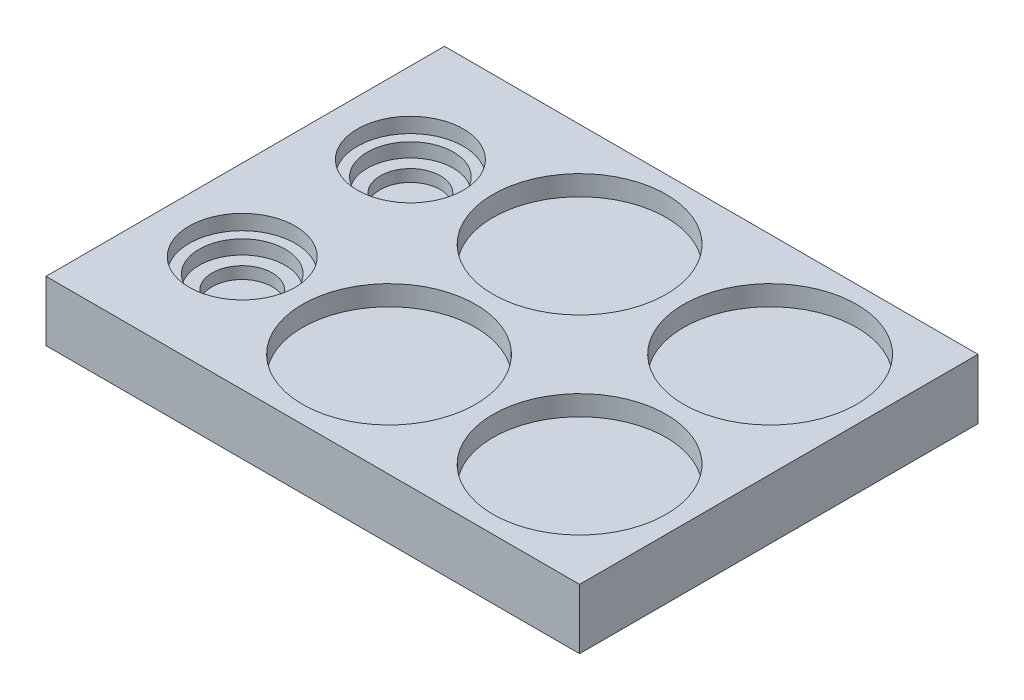
SolidWorks part; units mm, degrees
ref_plane "Спереди" through (0, 0, 0) normal (0, 0, 1) x (1, 0, 0)
ref_plane "Сверху" through (0, 0, 0) normal (0, 1, 0) x (1, 0, 0)
ref_plane "Справа" through (0, 0, 0) normal (1, 0, 0) x (0, 0, -1)
sketch "Эскиз1" plane through (0, 0, 0) normal (0, 1, 0) x (1, 0, 0)
  line L1 (0, 398) -> (533, 398)
  line L2 (0, 398) -> (0, 0)
  line L3 (0, 0) -> (533, 0)
  line L4 (533, 398) -> (533, 0)
  point P4 (0, 0)
  point P6 (0, 0)
  dimension "D1" = 533
  dimension "D2" = 398
extrude "Наполнитель" add sketch "Эскиз1" against normal blind 60
sketch "Эскиз2" plane through (0, 0, 0) normal (0, 1, 0) x (1, 0, 0)
  line L0 (429.1667, 380.6667) -> (429.1667, 398) construction
  line L1 (533, 398) -> (0, 398) construction
  line L2 (429.1667, 17.3333) -> (429.1667, 0) construction
  line L3 (0, 0) -> (533, 0) construction
  line L4 (515.6667, 294.1667) -> (533, 294.1667) construction
  line L5 (533, 0) -> (533, 398) construction
  line L6 (515.6667, 103.8333) -> (533, 103.8333) construction
  line L7 (238.8333, 207.6667) -> (238.8333, 190.3333) construction
  line L8 (325.3333, 294.1667) -> (342.6667, 294.1667) construction
  line L9 (325.3333, 103.8333) -> (342.6667, 103.8333) construction
  line L10 (429.1667, 207.6667) -> (429.1667, 190.3333) construction
  circle A0 centre (429.1667, 103.8333) radius 86.5
  circle A1 centre (238.8333, 103.8333) radius 86.5
  circle A2 centre (238.8333, 294.1667) radius 86.5
  circle A3 centre (429.1667, 294.1667) radius 86.5
  dimension "D1" = 173
  dimension "D2" = 2
  dimension "D3" = 2
extrude "Р597" cut sketch "Эскиз2" against normal blind 20
sketch "Эскиз3" plane through (0, 0, 0) normal (0, 1, 0) x (1, 0, 0)
  line L0 (81, 336) -> (81, 398) construction
  line L1 (533, 398) -> (0, 398) construction
  line L2 (28, 283) -> (0, 283) construction
  line L3 (0, 398) -> (0, 0) construction
  line L4 (81, 62) -> (81, 0) construction
  line L5 (0, 0) -> (533, 0) construction
  line L6 (28, 115) -> (0, 115) construction
  line L7 (81, 230) -> (81, 168) construction
  circle A0 centre (81, 283) radius 53
  circle A1 centre (81, 115) radius 53
  dimension "D2" = 106
  dimension "D4" = 28
  dimension "D1" = 2
extrude "КМЕ-101" cut sketch "Эскиз3" against normal blind 15
sketch "Эскиз6" plane through (0, -15, 0) normal (0, 1, 0) x (1, 0, 0)
  line L0 (81, 336) -> (81, 230) construction
  line L1 (28, 115) -> (134, 115) construction
  line L2 (81, 168) -> (81, 62) construction
  circle A0 centre (81, 283) radius 53 construction
  circle A1 centre (81, 283) radius 53 construction
  circle A2 centre (81, 283) radius 43
  circle A3 centre (81, 115) radius 43
  circle A4 centre (81, 115) radius 53 construction
  circle A5 centre (81, 115) radius 53 construction
  point P18 (81, 115)
  point P19 (0, 0)
  dimension "D1" = 86
  dimension "D2" = 2
extrude "Вырез-Вытянуть5" cut sketch "Эскиз6" against normal blind 14
sketch "Эскиз7" plane through (0, -29, 0) normal (0, 1, 0) x (1, 0, 0)
  line L0 (81, 336) -> (81, 230) construction
  line L1 (28, 283) -> (134, 283) construction
  line L2 (28, 115) -> (134, 115) construction
  line L3 (81, 168) -> (81, 62) construction
  circle A0 centre (81, 283) radius 53 construction
  circle A1 centre (81, 283) radius 53 construction
  circle A2 centre (81, 283) radius 30
  circle A3 centre (81, 115) radius 30
  circle A4 centre (81, 115) radius 53 construction
  circle A5 centre (81, 115) radius 53 construction
  point P11 (81, 283)
  point P23 (81, 115)
  dimension "D2" = 60
  dimension "D1" = 2
extrude "Вырез-Вытянуть6" cut sketch "Эскиз7" against normal blind 12
